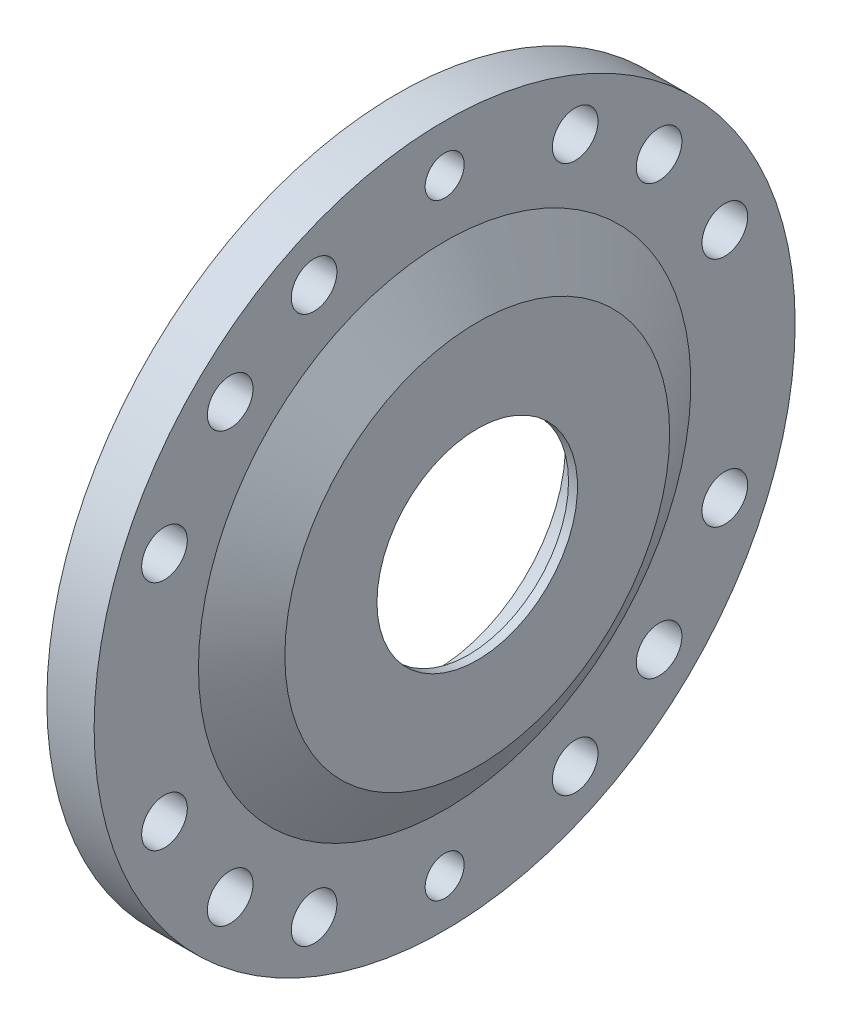
SolidWorks part; units mm, degrees
ref_plane "Plan de face" through (0, 0, 0) normal (0, 0, 1) x (1, 0, 0)
ref_plane "Plan de dessus" through (0, 0, 0) normal (0, 1, 0) x (1, 0, 0)
ref_plane "Plan de droite" through (0, 0, 0) normal (1, 0, 0) x (0, 0, -1)
sketch "Esquisse1" plane through (0, 0, 0) normal (0, 0, 1) x (1, 0, 0)
  line L0 (0, 0) -> (88.2928, 0)
  line L1 (88.2928, 0) -> (88.2928, 59)
  line L2 (88.2928, 59) -> (78.2928, 75.5)
  line L3 (78.2928, 75.5) -> (78.2928, 107.5)
  line L4 (78.2928, 107.5) -> (63.7928, 107.5)
  line L5 (63.7928, 107.5) -> (63.7928, 70)
  line L6 (63.7928, 70) -> (60.7928, 70)
  line L7 (60.7928, 70) -> (60.7928, 61)
  line L8 (60.7928, 61) -> (61.3989, 60)
  line L9 (61.3989, 60) -> (75.3478, 60)
  line L10 (75.3478, 60) -> (75.3478, 40)
  line L11 (75.3478, 40) -> (85.5364, 40)
  line L12 (85.5364, 40) -> (85.5364, 0)
  line L13 (85.5364, 0) -> (88.2928, 0)
  line L14 (85.5364, 0) -> (88.2928, 0)
  dimension "D1" = 107.5
  dimension "D2" = 70
  dimension "D3" = 61
  dimension "D4" = 75.5
  dimension "D5" = 59
  dimension "D6" = 60
  dimension "D7" = 27.5
  dimension "D8" = 3
  dimension "D9" = 14.5
  dimension "D10" = 40
revolve "Révolution1" add sketch "Esquisse1" angle 360 about L14
sketch "Esquisse2" plane through (63.7928, 0, 0) normal (-1, 0, 0) x (0, 0, 1)
  line L0 (0, 93) -> (0, -93)
  line L1 (-93, 0) -> (93, 0)
  line L2 (-40.0375, 83.9404) -> (0, 0)
  line L3 (-65.7609, 65.7609) -> (0, 0)
  line L4 (-85.9208, 35.5896) -> (0, 0)
  circle A0 centre (0, 0) radius 93
  circle A1 centre (-40.0375, 83.9404) radius 7
  circle A2 centre (-65.7609, 65.7609) radius 7
  circle A3 centre (-85.9208, 35.5896) radius 7
  circle A4 centre (40.0375, 83.9404) radius 7
  circle A5 centre (65.7609, 65.7609) radius 7
  circle A6 centre (85.9208, 35.5896) radius 7
  circle A7 centre (85.9208, -35.5896) radius 7
  circle A8 centre (65.7609, -65.7609) radius 7
  circle A9 centre (40.0375, -83.9404) radius 7
  circle A10 centre (-40.0375, -83.9404) radius 7
  circle A11 centre (-65.7609, -65.7609) radius 7
  circle A12 centre (-85.9208, -35.5896) radius 7
  circle A13 centre (0, 93) radius 5.983
  circle A14 centre (0, -93) radius 5.983
  dimension "D1" = 25.5
  dimension "186" = 186
  dimension "D4" = 14
  dimension "D5" = 14
  dimension "D6" = 14
  dimension "D7" = 11.966
  dimension "D2" = 45
  dimension "D3" = 67.5
extrude "Enlèv. mat.-Extru.1" cut sketch "Esquisse2" against normal through all contours A2 | A1 | A13 | A4 | A5 | A6 | A7 | A8 | A9 | A14 | A10 | A11 | A12 | A3
sketch "Esquisse3" plane through (75.3478, 0, 0) normal (-1, 0, 0) x (0, 0, 1)
  circle A1 centre (0, 0) radius 30.75
  dimension "D1" = 61.5
extrude "Enlèv. mat.-Extru.2" cut sketch "Esquisse3" against normal through all
fillet "Congé2" radius 1 1 edges at (60.7928, 0, 70)
fillet "Congé3" radius 2.5 1 edges at (75.3478, 0, 60)
